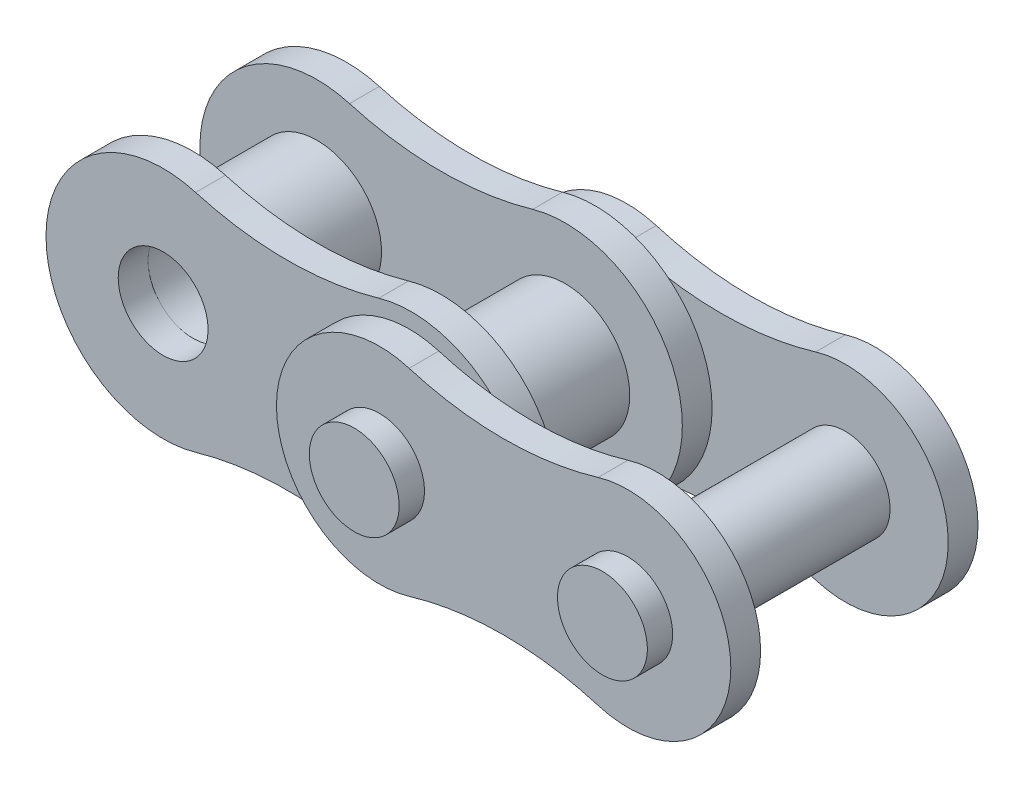
SolidWorks part; units mm, degrees
ref_plane "Front Plane" through (0, 0, 0) normal (0, 0, 1) x (1, 0, 0)
ref_plane "Top Plane" through (0, 0, 0) normal (0, 1, 0) x (1, 0, 0)
ref_plane "Right Plane" through (0, 0, 0) normal (1, 0, 0) x (0, 0, -1)
sketch "Sketch1" plane through (0, 0, 0) normal (0, 0, 1) x (1, 0, 0)
  line L0 (-3.175, 0) -> (3.175, 0) construction
  line L1 (-3.175, 2.9972) -> (-3.175, -2.9972) construction
  line L2 (0, -2.5476) -> (0, 2.5476) construction
  circle A0 centre (-3.175, 0) radius 1.651
  circle A1 centre (3.175, 0) radius 1.651
  circle A2 centre (-3.175, 0) radius 1.1493
  circle A3 centre (3.175, 0) radius 1.1493
  arc A4 (-2.3429, 2.8794) -> (-2.3429, -2.8794) centre (-3.175, 0) ccw
  arc A5 (2.3429, -2.8794) -> (2.3429, 2.8794) centre (3.175, 0) ccw
  arc A6 (-2.3429, 2.8794) -> (2.3429, 2.8794) centre (0, 10.9864) ccw
  arc A7 (-2.3429, -2.8794) -> (2.3429, -2.8794) centre (0, -10.9864) cw
  dimension "Roller Dia" = 3.302
  dimension "Pin Dia" = 2.2987
  dimension "Pitch" = 6.35
  dimension "H" = 5.9944
  dimension "D2" = 5.0952
sketch "Sketch2" plane through (0, 0, 0) normal (0, 1, 0) x (1, 0, 0)
  line L0 (0, 1.5875) -> (0, -1.5875) construction
  point P2 (0, -2.3495)
  point P4 (0, 2.3495)
  point P5 (0, 2.4003)
  point P6 (0, 3.1623)
  dimension "W" = 3.175
  dimension "T" = 0.762
  dimension "D1" = 0.762
  dimension "D2" = 0.762
  dimension "D3" = 0.0508
ref_plane "Plane1" through (0, 0, 1.5875) normal (0, 0, 1) x (1, 0, 0)
ref_plane "Plane2" through (0, 0, -2.4003) normal (0, 0, 1) x (1, 0, 0)
sketch "Sketch4" plane through (0, 0, 0) normal (0, 0, 1) x (1, 0, 0)
  circle A0 centre (-3.175, 0) radius 1.651 construction
  circle A1 centre (-3.175, 0) radius 1.651
  circle A2 centre (3.175, 0) radius 1.651 construction
  circle A3 centre (3.175, 0) radius 1.651
  circle A4 centre (-3.175, 0) radius 1.1747
  circle A5 centre (3.175, 0) radius 1.1747
  dimension "D1" = 2.3495
  dimension "D2" = 2.3495
extrude "Boss-Extrude1" add sketch "Sketch4" along normal mid plane 3.175
sketch "Sketch5" plane through (0, 0, 1.5875) normal (0, 0, 1) x (1, 0, 0)
  arc A0 (-2.3429, 2.8794) -> (-2.3429, -2.8794) centre (-3.175, 0) ccw construction
  arc A1 (-2.3429, 2.8794) -> (2.3429, 2.8794) centre (0, 10.9864) ccw construction
  circle A2 centre (-3.175, 0) radius 1.1493 construction
  arc A3 (2.3429, -2.8794) -> (2.3429, 2.8794) centre (3.175, 0) ccw construction
  circle A4 centre (3.175, 0) radius 1.1493 construction
  arc A5 (2.3429, -2.8794) -> (-2.3429, -2.8794) centre (0, -10.9864) ccw construction
  arc A6 (-2.3429, 2.8794) -> (-2.3429, -2.8794) centre (-3.175, 0) ccw
  arc A7 (-2.3429, 2.8794) -> (2.3429, 2.8794) centre (0, 10.9864) ccw
  circle A8 centre (-3.175, 0) radius 1.1493
  arc A9 (2.3429, -2.8794) -> (2.3429, 2.8794) centre (3.175, 0) ccw
  circle A10 centre (3.175, 0) radius 1.1493
  arc A11 (2.3429, -2.8794) -> (-2.3429, -2.8794) centre (0, -10.9864) ccw
extrude "Boss-Extrude2" add sketch "Sketch5" along normal up to vertex (0.762 mm away) separate body up to point (0, 0, 2.3495)
pattern_linear "LPattern1" count 2 spacing 6.35 along (1, 0, 0) of bodies 102
sketch "Sketch7" plane through (0, 0, -2.4003) normal (0, 0, 1) x (1, 0, 0)
  line L0 (9.525, 2.6375) -> (9.525, -2.6375) construction
  arc A0 (3.931, 2.5269) -> (3.931, -2.5269) centre (3.175, 0) ccw
  arc A1 (8.769, -2.5269) -> (8.769, 2.5269) centre (9.525, 0) ccw
  arc A2 (2.3429, -2.8794) -> (2.3429, 2.8794) centre (3.175, 0) ccw construction
  circle A3 centre (9.525, 0) radius 1.651 construction
  arc A4 (3.931, 2.5269) -> (8.769, 2.5269) centre (6.35, 10.6115) ccw
  arc A5 (3.931, -2.5269) -> (8.769, -2.5269) centre (6.35, -10.6115) cw
  arc A6 (-2.3429, 2.8794) -> (2.3429, 2.8794) centre (0, 10.9864) ccw construction
  circle A7 centre (3.175, 0) radius 1.1493 construction
  circle A8 centre (3.175, 0) radius 1.1493
  circle A9 centre (9.525, 0) radius 1.1493
  dimension "D2" = 5.2751
extrude "Boss-Extrude3" add sketch "Sketch7" against normal up to vertex (0.762 mm away) separate body up to point (0, 0, -3.1623)
mirror "Mirror1" about plane through (0, 0, 0) normal (0, 0, 1) of bodies 103 105
sketch "Sketch8" plane through (0, 0, 0) normal (0, 0, 1) x (1, 0, 0)
  circle A0 centre (3.175, 0) radius 1.1493
  circle A1 centre (9.525, 0) radius 1.1493
  circle A2 centre (3.175, 0) radius 1.1493 construction
  circle A3 centre (9.525, 0) radius 1.1494 construction
extrude "Boss-Extrude4" add sketch "Sketch8" against normal blind 3.81 and the other way blind 3.81 separate body
pattern_linear "LPattern2" [suppressed] count 2 spacing 12.7 along (1, 0, 0)
delete or keep bodies "Body-Delete1" [suppressed] type delete bodies bodies 115
combine bodies "Combine1" [suppressed] operation type add bodies to combine 102 103 104 105 106 107 108 109 110 111 112 113 114 116 117 118 101
sketch "Sketch9" [suppressed] plane through (0, 0, 0) normal (0, 0, 1) x (1, 0, 0)
  line L0 (22.225, 2.6375) -> (22.225, -2.6375) construction
  line L1 (15.875, 2.9972) -> (15.875, -2.9972) construction
  arc A0 (15.0429, -2.8794) -> (15.0429, 2.8794) centre (15.875, 0) ccw construction
  arc A1 (15.875, -2.9972) -> (15.875, 2.9972) centre (15.875, 0) ccw
  arc A2 (21.469, -2.5269) -> (21.469, 2.5269) centre (22.225, 0) ccw construction
  arc A3 (22.225, -2.6375) -> (22.225, 2.6375) centre (22.225, 0) ccw
  circle A4 centre (-3.175, 0) radius 1.651 construction
  circle A5 centre (-3.175, 0) radius 1.651
combine bodies "Combine2" operation type add bodies to combine 101 102 103 106
delete or keep bodies "Body-Delete/Keep 1" type delete bodies bodies 104
combine bodies "Combine3" operation type add bodies to combine 108 107 109 105
split "Split1" bodies to split 120 121 resulting bodies 122 123
equation "\"D2@Sketch1\" =\"H@Sketch1\"*.85"
equation "\"D1@Sketch2\" = \"T@Sketch2\""
equation "\"D1@Sketch4\" = \"Pin Dia@Sketch1\"+.002"
equation "\"D2@Sketch4\" = \"D1@Sketch4\""
equation "\"D1@Boss-Extrude1\" = \"W@Sketch2\""
equation "\"D2@Sketch2\" = \"T@Sketch2\""
equation "\"D3@LPattern1\" = \"Pitch@Sketch1\""
equation "\"D3@LPattern2\" = \"Pitch@Sketch1\"*2"
equation "\"D2@Sketch7\" = \"H@Sketch1\"*.88"
